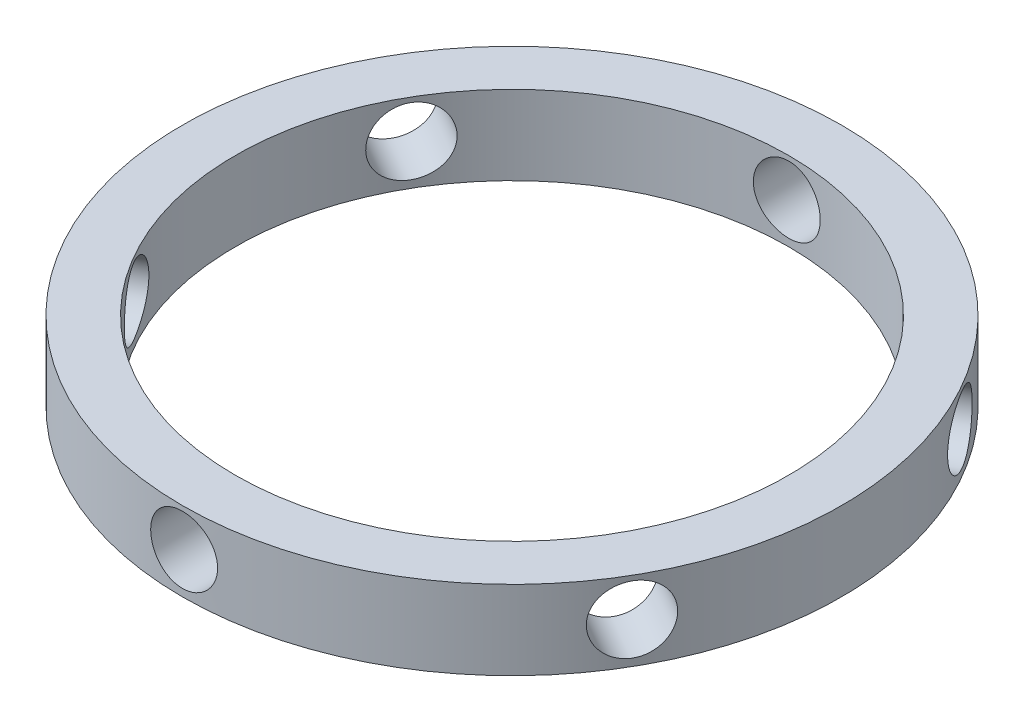
SolidWorks part; units mm, degrees
ref_plane "前视基准面" through (0, 0, 0) normal (0, 0, 1) x (1, 0, 0)
ref_plane "上视基准面" through (0, 0, 0) normal (0, 1, 0) x (1, 0, 0)
ref_plane "右视基准面" through (0, 0, 0) normal (1, 0, 0) x (0, 0, -1)
sketch "草图1" plane through (0, 0, 0) normal (0, 1, 0) x (1, 0, 0)
  circle A0 centre (0, 0) radius 50
  dimension "D1" = 100
extrude "凸台-拉伸1" add sketch "草图1" along normal blind 12
sketch "草图4" plane through (0, 0, 0) normal (0, 0, 1) x (1, 0, 0)
  circle A0 centre (0, 6.1916) radius 5.075
  dimension "D1" = 10.15
sketch "草图24" plane through (0, 12, 0) normal (0, 1, 0) x (1, 0, 0)
  circle A0 centre (0, 0) radius 50
  dimension "D1" = 100
extrude "切除-拉伸5" cut sketch "草图4" against normal through all contours A0
pattern_circular "阵列(圆周)3" count 6 over 360 about axis through (0, 0, 0) along (0, 1, 0) of "切除-拉伸5"
sketch "草图27" plane through (0, 0, 0) normal (0, -1, 0) x (1, 0, 0)
  circle A0 centre (0, 0) radius 42
  dimension "D1" = 84
extrude "切除-拉伸7" cut sketch "草图27" against normal through all
